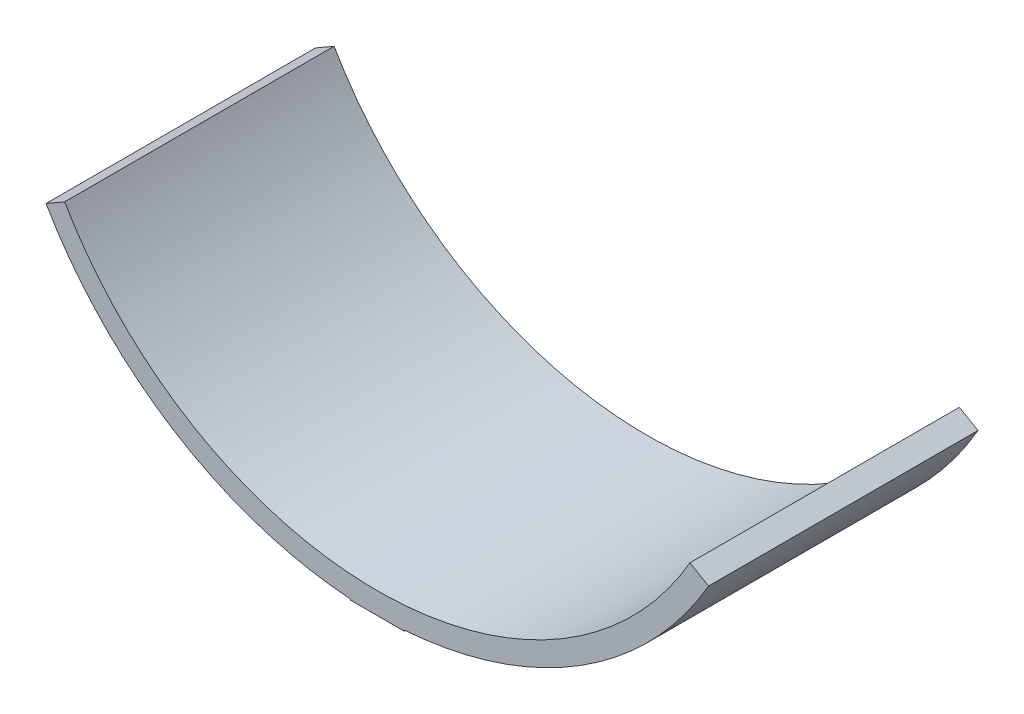
SolidWorks part; units mm, degrees
ref_plane "Front Plane" through (0, 0, 0) normal (0, 0, 1) x (1, 0, 0)
ref_plane "Top Plane" through (0, 0, 0) normal (0, 1, 0) x (1, 0, 0)
ref_plane "Right Plane" through (0, 0, 0) normal (1, 0, 0) x (0, 0, -1)
sketch "Sketch1" plane through (0, 0, 0) normal (0, 0, 1) x (1, 0, 0)
  line L0 (0, -2.54) -> (0, 2.54)
  line L1 (-6.35, -2.54) -> (6.35, -2.54)
  line L2 (-6.35, -2.54) -> (-6.35, 2.54)
  line L3 (-6.35, 2.54) -> (6.35, 2.54)
  line L4 (6.35, -2.54) -> (6.35, 2.54)
  line L5 (-6.35, -2.54) -> (6.35, 2.54) construction
  line L6 (-6.35, 2.54) -> (6.35, -2.54) construction
  line L7 (0, 2.54) -> (0, 129.54) construction
  line L10 (0, 87.63) -> (-97.1594, 31.535) construction
  line L11 (0, 87.63) -> (119.4251, 18.6799) construction
  line L12 (-73.6901, 45.085) -> (-78.0895, 42.545)
  line L13 (78.0895, 42.545) -> (73.6901, 45.085)
  arc A0 (-73.6901, 45.085) -> (73.6901, 45.085) centre (0, 87.63) ccw
  arc A1 (-78.0895, 42.545) -> (78.0895, 42.545) centre (0, 87.63) ccw
  point P0 (0, 0)
  dimension "D2" = 85.09
  dimension "D1" = 5.08
  dimension "0.5" = 12.7
  dimension "D5" = 60
  dimension "D6" = 60
extrude "Boss-Extrude1" add sketch "Sketch1" along normal blind 63.5
sketch "Sketch2" plane through (0, -2.54, 0) normal (0, -1, 0) x (1, 0, 0)
  line L1 (-2.5527, 25.273) -> (2.7813, 25.273)
  line L2 (-2.5527, 25.273) -> (-2.5527, 56.007)
  line L3 (-2.5527, 56.007) -> (2.7813, 56.007)
  line L4 (2.7813, 25.273) -> (2.7813, 56.007)
  line L5 (-2.5527, 25.273) -> (2.7813, 56.007) construction
  line L6 (-2.5527, 56.007) -> (2.7813, 25.273) construction
  line L7 (-6.35, 63.5) -> (-6.35, 0) construction
  line L8 (-6.35, 63.5) -> (6.35, 63.5) construction
  point P0 (0.1143, 40.64)
  dimension "D1" = 5.334
  dimension "D2" = 30.734
  dimension "D3" = 7.493
  dimension "D4" = 3.7973
extrude "Cut-Extrude1" cut sketch "Sketch2" against normal blind 3.175
